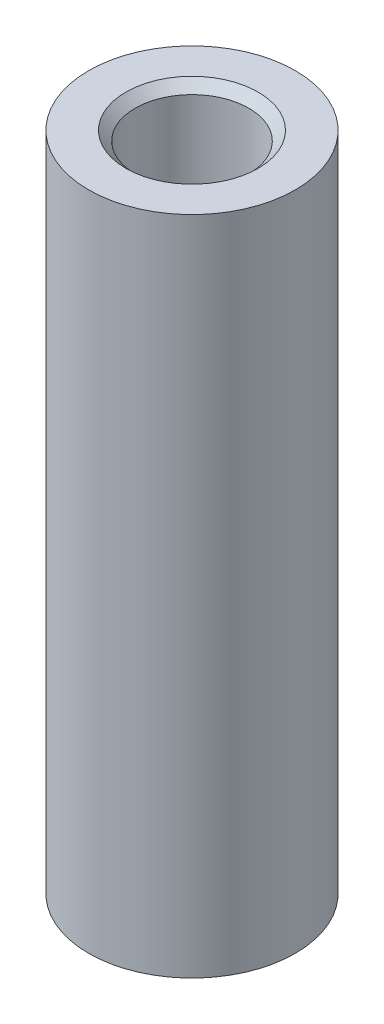
SolidWorks part; units mm, degrees
ref_plane "Front Plane" through (0, 0, 0) normal (1, 0, 0) x (0, 1, 0)
ref_plane "Top Plane" through (0, 0, 0) normal (0, 0, 1) x (0, 1, 0)
ref_plane "Right Plane" through (0, 0, 0) normal (0, 1, 0) x (-1, 0, 0)
sketch "Sketch1" plane through (0, 0, 0) normal (0, 1, 0) x (-1, 0, 0)
  circle A0 centre (0, 0) radius 15.875
  dimension "D2" = 31.75
extrude "Boss-Extrude1" add sketch "Sketch1" along normal blind 101.6
sketch "Sketch2" plane through (0, 0, 0) normal (0, 0, 1) x (0, 1, 0)
  line L1 (-13.97, 0) -> (13.97, 0) construction
  line L3 (0, -13.97) -> (0, 13.97) construction
  line L4 (0, -6.35) -> (0, 0)
  line L5 (0, -6.35) -> (4.8627, -6.35)
  line L6 (4.8627, -6.35) -> (8.6781, 0)
  line L7 (0, 0) -> (8.6781, 0)
  circle A0 centre (1.27, 0) radius 6.35 construction
  dimension "D4" = 12.7
  dimension "D1" = 1.27
  dimension "D2" = 6.35
  dimension "D3" = 59
revolve "Cut-Revolve1" cut sketch "Sketch2" angle 360 about L7
sketch "Sketch3" plane through (0, 101.6, 0) normal (0, 1, 0) x (-1, 0, 0)
  circle A0 centre (0, 0) radius 2.5681 construction
  dimension "D1" = 5.1361
hole_wizard "3/4-16 Tapped Hole1" positions "Sketch6" profile "Sketch7" tap size "3/4-16" standard "ANSI Inch"
sketch "Sketch6" plane through (0, 101.6, 0) normal (0, 1, 0) x (-1, 0, 0)
  point P0 (0, 0)
sketch "Sketch7" plane through (0, 101.6, 0) normal (1, 0, 0) x (0, 0, 1)
  line L0 (0, 0) -> (0, 48.1723)
  line L1 (0, 48.1723) -> (8.7312, 42.926)
  line L2 (8.7312, 42.926) -> (8.7312, 1.4288)
  line L3 (8.7312, 1.4288) -> (10.16, 0)
  line L5 (10.16, 0) -> (0, 0)
  line L6 (-8.7312, 1.4288) -> (-10.16, 0) construction
  line L10 (0, 48.1723) -> (-8.7313, 42.926) construction
  line L11 (0, -6.35) -> (0, 107.95) construction
  dimension "Tap Drill Dia." = 17.4625
  dimension "Tap Drill Depth" = 42.926
  dimension "Near C'Sink Dia." = 20.32
  dimension "Near C'Sink Angle" = 90
  dimension "Drill Angle" = 118
cosmetic thread "Hole Thread1" parameters "D1"=38.1, "D2"=19.05
